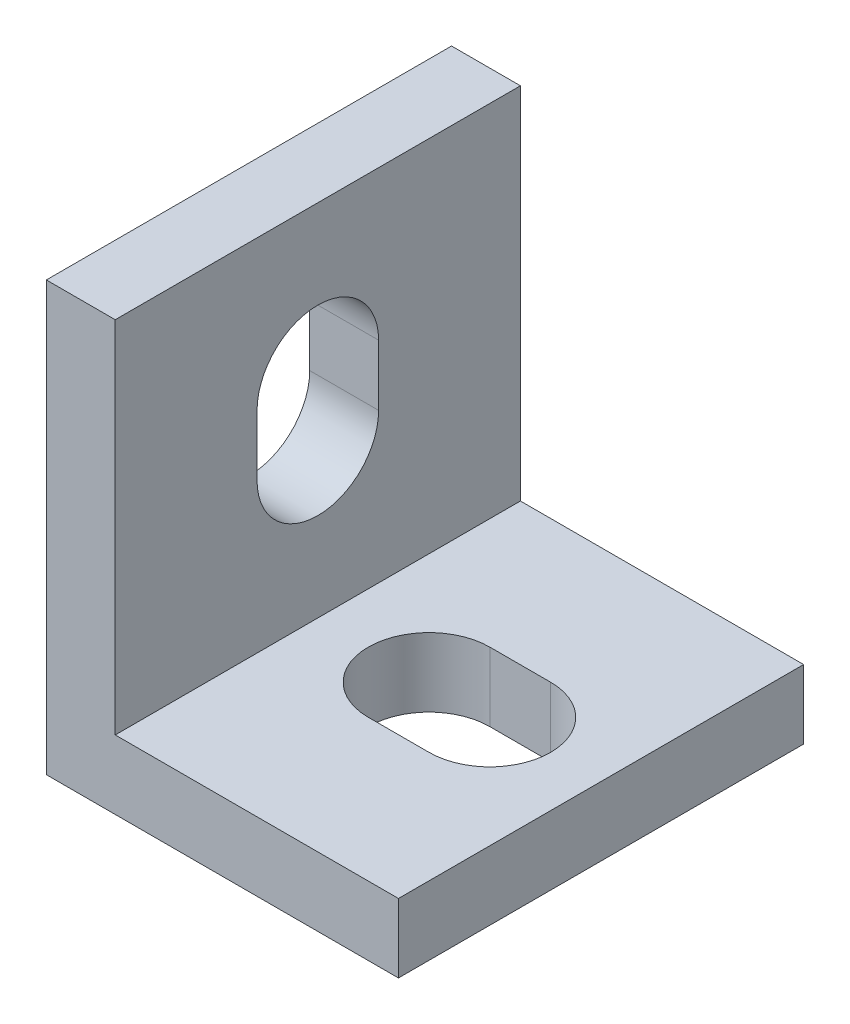
SolidWorks part; units mm, degrees
ref_plane "Front Plane" through (0, 0, 0) normal (0, 0, 1) x (1, 0, 0)
ref_plane "Top Plane" through (0, 0, 0) normal (0, 1, 0) x (1, 0, 0)
ref_plane "Right Plane" through (0, 0, 0) normal (1, 0, 0) x (0, 0, -1)
sketch "Sketch1" plane through (0, 0, 0) normal (0, 0, 1) x (1, 0, 0)
  line L0 (0, 0) -> (17.38, 0)
  line L1 (0, 0) -> (0, 21.15)
  line L2 (0, 21.15) -> (3.4, 21.15)
  line L4 (17.38, 3.4) -> (17.38, 0)
  line L5 (17.38, 3.4) -> (3.4, 3.4)
  line L6 (3.4, 3.4) -> (3.4, 21.15)
  dimension "D1" = 17.38
  dimension "D2" = 21.15
  dimension "D3" = 3.4
  dimension "D4" = 3.4
extrude "Boss-Extrude2" add sketch "Sketch1" along normal blind 20
sketch "Sketch2" plane through (3.4, 0, 0) normal (1, 0, 0) x (0, 0, -1)
  line L0 (-10, 13.775) -> (-10, 10.775) construction
  line L1 (-7, 13.775) -> (-7, 10.775)
  line L2 (-13, 13.775) -> (-13, 10.775)
  line L3 (0, 3.4) -> (0, 21.15) construction
  line L4 (-20, 21.15) -> (0, 21.15) construction
  arc A0 (-7, 13.775) -> (-13, 13.775) centre (-10, 13.775) ccw
  arc A1 (-13, 10.775) -> (-7, 10.775) centre (-10, 10.775) ccw
  point P2 (-10, 12.275)
  point P9 (-10, 16.775)
  point P10 (-10, 7.775)
  dimension "D1" = 6
  dimension "D2" = 10
  dimension "D3" = 9
  dimension "D4" = 8.875
extrude "Cut-Extrude1" cut sketch "Sketch2" against normal blind 20
sketch "Sketch3" plane through (0, 3.4, 0) normal (0, 1, 0) x (1, 0, 0)
  line L0 (8.89, -10) -> (11.89, -10) construction
  line L1 (8.89, -7) -> (11.89, -7)
  line L2 (8.89, -13) -> (11.89, -13)
  line L4 (17.38, 0) -> (3.4, 0) construction
  line L6 (17.38, -20) -> (17.38, 0) construction
  arc A0 (8.89, -7) -> (8.89, -13) centre (8.89, -10) ccw
  arc A1 (11.89, -13) -> (11.89, -7) centre (11.89, -10) ccw
  point P2 (10.39, -10)
  point P7 (14.89, -10)
  point P8 (5.89, -10)
  point P15 (17.38, -10)
  dimension "D1" = 6
  dimension "D2" = 9
  dimension "D3" = 10
  dimension "D4" = 6.99
extrude "Cut-Extrude2" cut sketch "Sketch3" against normal blind 20
